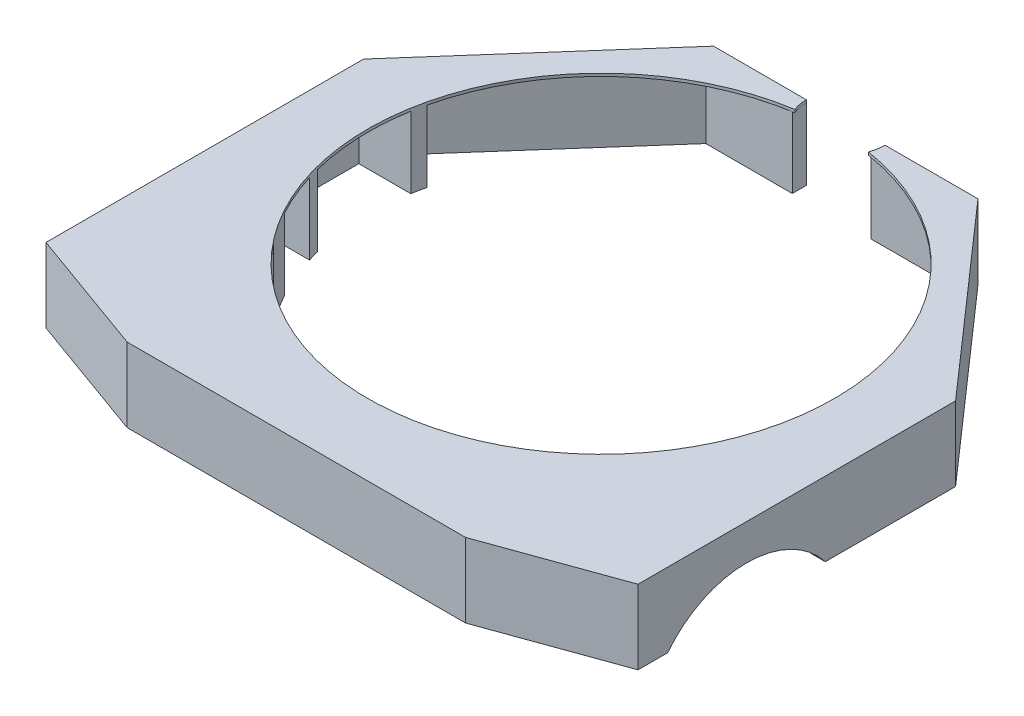
SolidWorks part; units mm, degrees
ref_plane "Front Plane" through (0, 0, 0) normal (0, 0, 1) x (1, 0, 0)
ref_plane "Top Plane" through (0, 0, 0) normal (0, 1, 0) x (1, 0, 0)
ref_plane "Right Plane" through (0, 0, 0) normal (1, 0, 0) x (0, 0, -1)
sketch "Sketch1" plane through (0, 0, 0) normal (0, 1, 0) x (1, 0, 0)
  line L0 (-304.5074, 63.6631) -> (-304.5074, -102.7433)
  line L1 (-304.5074, -102.7433) -> (-191.8567, -143.3381)
  line L2 (-191.8567, -143.3381) -> (108.842, -143.3381)
  line L3 (108.842, -143.3381) -> (221.4926, -102.7433)
  line L4 (221.4926, -102.7433) -> (221.4926, 63.6631)
  line L5 (-304.5074, 63.6631) -> (-302.0074, 63.6631)
  line L6 (-302.0074, -100.9868) -> (-191.42, -140.8381)
  line L7 (-191.42, -140.8381) -> (108.4053, -140.8381)
  line L8 (108.4053, -140.8381) -> (218.9926, -100.9868)
  line L9 (218.9926, -100.9868) -> (218.9926, 63.6631)
  line L10 (221.4926, 63.6631) -> (218.9926, 63.6631)
  line L11 (-302.0074, -100.9868) -> (-302.0074, 63.6631)
  dimension "D1" = 2.5
  dimension "D2" = 2.5
  dimension "D3" = 166.4064
  dimension "D4" = 2.5
  dimension "D5" = 2.5
  dimension "D6" = 2.5
  dimension "D7" = 119.7418
  dimension "D8" = 119.7418
  dimension "D9" = 300.6987
  dimension "D10" = 160.183
extrude "Boss-Extrude1" add sketch "Sketch1" along normal blind 63.4
sketch "Sketch2" plane through (-304.5074, 0, 0) normal (-1, 0, 0) x (0, 0, 1)
  line L2 (-63.6631, 0) -> (102.7433, 0) construction
  line L4 (102.7433, 0) -> (76.3394, 0)
  circle A1 centre (6.3381, -54.8) radius 88.9
  line M1 (-63.6631, 0) -> (102.7433, 0)
  dimension "D1" = 177.8
  dimension "D3" = 26.404
sketch "Sketch3" plane through (0, 0, 0) normal (0, 1, 0) x (1, 0, 0)
  line L1 (-304.5074, 179.4163) -> (-159.0118, 344.8175)
  line L2 (221.4926, 179.4163) -> (75.9971, 344.8175)
  line L16 (-304.5074, 63.6631) -> (-304.5074, 179.4163)
  line L17 (221.4926, 63.6631) -> (221.4926, 179.4163)
  line L19 (-159.0118, 344.8175) -> (75.9971, 344.8175)
  line L20 (-302.0074, 63.6631) -> (-302.0074, 178.4732)
  line L21 (-302.0074, 178.4732) -> (-157.8814, 342.3175)
  line L22 (-157.8814, 342.3175) -> (74.8666, 342.3175)
  line L23 (218.9926, 178.4732) -> (74.8666, 342.3175)
  line L24 (218.9926, 63.6631) -> (218.9926, 178.4732)
  line L25 (-304.5074, 63.6631) -> (-302.0074, 63.6631)
  line L26 (218.9926, 63.6631) -> (221.4926, 63.6631)
  dimension "D1" = 115.7533
  dimension "D2" = 220.2873
  dimension "D3" = 221.337
  dimension "D4" = 221.337
  dimension "D5" = 2.5
extrude "Boss-Extrude2" add sketch "Sketch3" along normal up to surface (63.4 mm away) separate body contours L17 L2 L19 L1 L16 L25 L20 L21 L22 L23 L24 L26 up to face at (-41.5074, 63.4, 60.0967)
sketch "Sketch5" plane through (0, 0, 0) normal (0, 1, 0) x (1, 0, 0)
  line L25 (208.9926, 174.7009) -> (208.9926, 63.6631)
  line L26 (70.3448, 332.3175) -> (208.9926, 174.7009)
  line L27 (-153.3595, 332.3175) -> (70.3448, 332.3175)
  line L28 (-292.0074, 174.7009) -> (-153.3595, 332.3175)
  line L29 (-292.0074, 63.6631) -> (-292.0074, 174.7009)
  line L30 (208.9926, 174.7009) -> (208.9926, 63.6631)
  line L31 (70.3448, 332.3175) -> (208.9926, 174.7009)
  line L32 (-153.3595, 332.3175) -> (70.3448, 332.3175)
  line L33 (-292.0074, 174.7009) -> (-153.3595, 332.3175)
  line L34 (-292.0074, 63.6631) -> (-292.0074, 174.7009)
  line L45 (-302.0074, 63.6631) -> (-292.0074, 63.6631)
  line L46 (208.9926, 63.6631) -> (218.9926, 63.6631)
  line L50 (218.9926, 178.4732) -> (218.9926, 63.6631)
  line L51 (74.8666, 342.3175) -> (218.9926, 178.4732)
  line L52 (-157.8814, 342.3175) -> (74.8666, 342.3175)
  line L53 (-302.0074, 178.4732) -> (-157.8814, 342.3175)
  line L54 (-302.0074, 63.6631) -> (-302.0074, 178.4732)
  line L55 (218.9926, 178.4732) -> (218.9926, 63.6631)
  line L56 (74.8666, 342.3175) -> (218.9926, 178.4732)
  line L57 (-157.8814, 342.3175) -> (74.8666, 342.3175)
  line L58 (-302.0074, 178.4732) -> (-157.8814, 342.3175)
  line L59 (-302.0074, 63.6631) -> (-302.0074, 178.4732)
  line L63 (215.6024, -91.5791) -> (106.6585, -130.8381)
  line L64 (106.6585, -130.8381) -> (-189.6732, -130.8381)
  line L65 (-189.6732, -130.8381) -> (-298.6172, -91.5791)
  line L66 (218.9926, -100.9868) -> (108.4053, -140.8381)
  line L67 (108.4053, -140.8381) -> (-191.42, -140.8381)
  line L68 (-191.42, -140.8381) -> (-302.0074, -100.9868)
  line L69 (218.9926, -100.9868) -> (108.4053, -140.8381)
  line L70 (108.4053, -140.8381) -> (-191.42, -140.8381)
  line L71 (-191.42, -140.8381) -> (-302.0074, -100.9868)
  line L72 (-298.6172, -91.5791) -> (-302.0074, -100.9868)
  line L73 (215.6024, -91.5791) -> (218.9926, -100.9868)
  dimension "D1" = 10
  dimension "D2" = 0
  dimension "D3" = 0
  dimension "D4" = 10
extrude "Boss-Extrude3" add sketch "Sketch5" along normal blind 5
sketch "Sketch6" plane through (0, 63.4, 0) normal (0, 1, 0) x (1, 0, 0)
  line L16 (-159.0118, 344.8175) -> (-304.5074, 179.4163)
  line L17 (-304.5074, 179.4163) -> (-304.5074, -102.7433)
  line L18 (-304.5074, -102.7433) -> (-191.8567, -143.3381)
  line L19 (-191.8567, -143.3381) -> (108.842, -143.3381)
  line L20 (108.842, -143.3381) -> (221.4926, -102.7433)
  line L21 (221.4926, -102.7433) -> (221.4926, 179.4163)
  line L22 (221.4926, 179.4163) -> (75.9971, 344.8175)
  line L23 (75.9971, 344.8175) -> (-159.0118, 344.8175)
  line L24 (-159.0118, 344.8175) -> (-304.5074, 179.4163)
  line L25 (-304.5074, 179.4163) -> (-304.5074, -102.7433)
  line L26 (-304.5074, -102.7433) -> (-191.8567, -143.3381)
  line L27 (-191.8567, -143.3381) -> (108.842, -143.3381)
  line L28 (108.842, -143.3381) -> (221.4926, -102.7433)
  line L29 (221.4926, -102.7433) -> (221.4926, 179.4163)
  line L30 (221.4926, 179.4163) -> (75.9971, 344.8175)
  line L31 (75.9971, 344.8175) -> (-159.0118, 344.8175)
  dimension "D1" = 0
extrude "Boss-Extrude4" add sketch "Sketch6" along normal blind 2.5
sketch "Sketch7" plane through (0, 5, 0) normal (0, 1, 0) x (1, 0, 0)
  line L0 (106.6585, -130.8381) -> (-189.6732, -130.8381) construction
  line L1 (-52.15, -130.8381) -> (-42.15, -130.8381)
  line L2 (-52.15, -130.8381) -> (-52.15, -140.8381)
  line L3 (-52.15, -140.8381) -> (-42.15, -140.8381)
  line L4 (-42.15, -130.8381) -> (-42.15, -140.8381)
  line L5 (-191.42, -140.8381) -> (108.4053, -140.8381) construction
  line L7 (76.7898, -130.8381) -> (86.7898, -130.8381)
  line L8 (76.7898, -130.8381) -> (76.7898, -140.8381)
  line L9 (76.7898, -140.8381) -> (86.7898, -140.8381)
  line L10 (86.7898, -130.8381) -> (86.7898, -140.8381)
  line L11 (-257.8308, -106.2769) -> (-261.221, -115.6847)
  line L12 (-178.361, -130.8381) -> (-168.361, -130.8381)
  line L13 (-178.361, -130.8381) -> (-178.361, -140.8381)
  line L14 (-178.361, -140.8381) -> (-168.361, -140.8381)
  line L15 (-168.361, -130.8381) -> (-168.361, -140.8381)
  line L16 (-189.6732, -130.8381) -> (-298.6172, -91.5791) construction
  line L17 (-302.0074, -100.9868) -> (-191.42, -140.8381) construction
  line L18 (-248.423, -109.6671) -> (-251.8132, -119.0748)
  line L19 (-251.8132, -119.0748) -> (-261.221, -115.6847)
  line L20 (-257.8308, -106.2769) -> (-248.423, -109.6671)
  line L21 (155.7814, -113.1362) -> (159.1716, -122.544)
  line L22 (215.6024, -91.5791) -> (106.6585, -130.8381) construction
  line L24 (159.1716, -122.544) -> (168.5794, -119.1538)
  line L25 (108.4053, -140.8381) -> (218.9926, -100.9868) construction
  line L26 (168.5794, -119.1538) -> (165.1892, -109.746)
  line L27 (165.1892, -109.746) -> (155.7814, -113.1362)
  line L28 (-302.0074, 178.4732) -> (-302.0074, 63.6631) construction
  line L34 (74.8666, 342.3175) -> (-157.8814, 342.3175) construction
  line L35 (-127.9155, 342.3175) -> (-117.9155, 342.3175)
  line L36 (-127.9155, 342.3175) -> (-127.9155, 332.3175)
  line L37 (-127.9155, 332.3175) -> (-117.9155, 332.3175)
  line L38 (-117.9155, 342.3175) -> (-117.9155, 332.3175)
  line L39 (-153.3595, 332.3175) -> (70.3448, 332.3175) construction
  line L41 (18.9775, 342.3175) -> (28.9775, 342.3175)
  line L42 (18.9775, 342.3175) -> (18.9775, 332.3175)
  line L43 (18.9775, 332.3175) -> (28.9775, 332.3175)
  line L44 (28.9775, 342.3175) -> (28.9775, 332.3175)
  line L45 (208.9926, 174.7009) -> (208.9926, 63.6631) construction
  line L46 (208.9926, 174.7009) -> (218.9926, 174.7009)
  line L47 (208.9926, 174.7009) -> (208.9926, 164.7009)
  line L48 (208.9926, 164.7009) -> (218.9926, 164.7009)
  line L49 (218.9926, 174.7009) -> (218.9926, 164.7009)
  line L50 (218.9926, 63.6631) -> (218.9926, 178.4732) construction
  line L51 (-263.7563, 221.9576) -> (-256.2478, 215.3528)
  line L52 (208.9926, 63.6631) -> (218.9926, 63.6631)
  line L53 (208.9926, 63.6631) -> (208.9926, 73.6631)
  line L54 (208.9926, 73.6631) -> (218.9926, 73.6631)
  line L55 (218.9926, 63.6631) -> (218.9926, 73.6631)
  line L56 (-292.0074, 63.6631) -> (-302.0074, 63.6631)
  line L57 (-292.0074, 63.6631) -> (-292.0074, 73.6631)
  line L58 (-292.0074, 73.6631) -> (-302.0074, 73.6631)
  line L59 (-302.0074, 63.6631) -> (-302.0074, 73.6631)
  line L60 (-292.0074, 174.7009) -> (-302.0074, 174.7009)
  line L61 (-292.0074, 174.7009) -> (-292.0074, 164.7009)
  line L62 (-292.0074, 164.7009) -> (-302.0074, 164.7009)
  line L63 (-302.0074, 174.7009) -> (-302.0074, 164.7009)
  line L64 (-157.8814, 342.3175) -> (-302.0074, 178.4732) construction
  line L65 (-292.0074, 174.7009) -> (-153.3595, 332.3175) construction
  line L66 (-256.2478, 215.3528) -> (-249.643, 222.8612)
  line L67 (-249.643, 222.8612) -> (-257.1515, 229.466)
  line L68 (-257.1515, 229.466) -> (-263.7563, 221.9576)
  line L69 (-209.6632, 283.4513) -> (-202.1548, 276.8465)
  line L71 (-202.1548, 276.8465) -> (-195.55, 284.3549)
  line L72 (-195.55, 284.3549) -> (-203.0584, 290.9597)
  line L73 (-203.0584, 290.9597) -> (-209.6632, 283.4513)
  line L74 (116.6943, 294.7673) -> (109.1858, 288.1625)
  line L76 (70.3448, 332.3175) -> (208.9926, 174.7009) construction
  line L77 (109.1858, 288.1625) -> (115.7906, 280.6541)
  line L78 (115.7906, 280.6541) -> (123.2991, 287.2589)
  line L79 (218.9926, 178.4732) -> (74.8666, 342.3175) construction
  line L80 (123.2991, 287.2589) -> (116.6943, 294.7673)
  line L81 (174.6268, 228.9089) -> (167.1183, 222.3041)
  line L82 (167.1183, 222.3041) -> (173.7231, 214.7957)
  line L83 (173.7231, 214.7957) -> (181.2316, 221.4005)
  line L84 (181.2316, 221.4005) -> (174.6268, 228.9089)
  dimension "D1" = 10
  dimension "D2" = 10
  dimension "D3" = 10
  dimension "D4" = 10
  dimension "D5" = 10
  dimension "D6" = 10
  dimension "D7" = 10
  dimension "D8" = 10
  dimension "D9" = 10
  dimension "D10" = 10
  dimension "D11" = 10
  dimension "D12" = 10
  dimension "D13" = 10
  dimension "D14" = 10
  dimension "D15" = 10
extrude "Boss-Extrude5" [suppressed] add sketch "Sketch7" along normal up to surface (58.4 mm away)
sketch "Sketch8" plane through (0, 0, -344.8175) normal (0, 0, -1) x (-1, 0, 0)
  line L0 (268.4856, 0) -> (-268.4856, 0) construction
  line L1 (6.5074, 0) -> (76.5074, 0)
  line L2 (6.5074, 0) -> (6.5074, 28.4)
  line L3 (6.5074, 28.4) -> (76.5074, 28.4)
  line L4 (76.5074, 0) -> (76.5074, 28.4)
  line L5 (-75.9971, 0) -> (6.5074, 0) construction
  line L6 (16.5074, 28.4) -> (66.5074, 28.4)
  line L7 (16.5074, 28.4) -> (16.5074, 63.4)
  line L8 (16.5074, 63.4) -> (66.5074, 63.4)
  line L9 (66.5074, 28.4) -> (66.5074, 63.4)
  line L10 (76.5074, 0) -> (159.0118, 0) construction
  line L12 (6.5074, 28.4) -> (16.5074, 28.4) construction
  line L13 (6.5074, 28.4) -> (6.5074, 37.3454) construction
  line L14 (6.5074, 37.3454) -> (16.5074, 37.3454) construction
  line L15 (16.5074, 28.4) -> (16.5074, 37.3454) construction
  line L16 (66.5074, 28.4) -> (76.5074, 28.4) construction
  line L17 (66.5074, 28.4) -> (66.5074, 37.3454) construction
  line L18 (66.5074, 37.3454) -> (76.5074, 37.3454) construction
  line L19 (76.5074, 28.4) -> (76.5074, 37.3454) construction
  line M4 (-75.9971, 0) -> (159.0118, 0)
  dimension "D1" = 70
  dimension "D2" = 50
  dimension "D3" = 63.4
  dimension "D4" = 28.4
extrude "Cut-Extrude2" cut sketch "Sketch8" along direction (0, 0, -1) on the side against the normal up to next (12.5 mm away) contours L4 L3 L2 M4 | L3 L9 L8 L7
sketch "Sketch9" plane through (0, 65.9, 0) normal (0, 1, 0) x (1, 0, 0)
  line L16 (75.9971, 344.8175) -> (-159.0118, 344.8175)
  line L17 (-159.0118, 344.8175) -> (-304.5074, 179.4163)
  line L18 (-304.5074, 179.4163) -> (-304.5074, -102.7433)
  line L19 (-304.5074, -102.7433) -> (-191.8567, -143.3381)
  line L20 (-191.8567, -143.3381) -> (108.842, -143.3381)
  line L21 (108.842, -143.3381) -> (221.4926, -102.7433)
  line L22 (221.4926, -102.7433) -> (221.4926, 179.4163)
  line L23 (221.4926, 179.4163) -> (75.9971, 344.8175)
  line L24 (75.9971, 344.8175) -> (-159.0118, 344.8175) construction
  line L25 (-159.0118, 344.8175) -> (-304.5074, 179.4163)
  line L26 (-304.5074, 179.4163) -> (-304.5074, -102.7433)
  line L27 (-304.5074, -102.7433) -> (-191.8567, -143.3381)
  line L28 (-191.8567, -143.3381) -> (108.842, -143.3381)
  line L29 (108.842, -143.3381) -> (221.4926, -102.7433)
  line L30 (221.4926, -102.7433) -> (221.4926, 179.4163)
  line L31 (221.4926, 179.4163) -> (75.9971, 344.8175)
  line L33 (-6.5074, 344.8175) -> (-16.5074, 344.8175)
  line L34 (-16.5074, 344.8175) -> (-66.5074, 344.8175)
  line L35 (-66.5074, 344.8175) -> (-76.5074, 344.8175)
  line L36 (-6.5074, 344.8175) -> (-16.5074, 344.8175) construction
  line L37 (-16.5074, 344.8175) -> (-66.5074, 344.8175) construction
  line L38 (-66.5074, 344.8175) -> (-76.5074, 344.8175) construction
  circle A0 centre (-41.5074, 344.8175) radius 35
  line M13 (75.9971, 344.8175) -> (-159.0118, 344.8175)
  dimension "D1" = 0
  dimension "D2" = 0
extrude "Cut-Extrude4" cut sketch "Sketch9" against normal up to surface (2.5 mm away) contours A0 M13
sketch "Sketch10" plane through (0, 0, -344.8175) normal (0, 0, -1) x (-1, 0, 0)
  line L1 (6.5074, 63.4) -> (16.5074, 63.4)
  line L2 (6.5074, 63.4) -> (6.5074, 28.4)
  line L3 (6.5074, 28.4) -> (16.5074, 28.4)
  line L4 (16.5074, 63.4) -> (16.5074, 28.4)
  line L5 (66.5074, 63.4) -> (76.5074, 63.4)
  line L6 (66.5074, 63.4) -> (66.5074, 28.4)
  line L7 (66.5074, 28.4) -> (76.5074, 28.4)
  line L8 (76.5074, 63.4) -> (76.5074, 28.4)
extrude "Cut-Extrude5" cut sketch "Sketch10" against normal up to surface (2.5 mm away) up to face at (13.8724, 36.7143, -342.3175)
sketch "Sketch11" plane through (0, 5, 0) normal (0, 1, 0) x (1, 0, 0)
  line L526 (-76.5074, 332.3175) -> (-76.5074, 342.3175)
  line L527 (-76.5074, 342.3175) -> (-157.8814, 342.3175)
  line L528 (-153.3595, 332.3175) -> (-76.5074, 332.3175)
  line L529 (-292.0074, 174.7009) -> (-153.3595, 332.3175)
  line L530 (-157.8814, 342.3175) -> (-302.0074, 178.4732)
  line L531 (-302.0074, 178.4732) -> (-302.0074, 63.6631)
  line L532 (-292.0074, 63.6631) -> (-292.0074, 174.7009)
  line L533 (-302.0074, 63.6631) -> (-292.0074, 63.6631)
  line L534 (-76.5074, 332.3175) -> (-76.5074, 342.3175)
  line L535 (-76.5074, 342.3175) -> (-157.8814, 342.3175)
  line L536 (-153.3595, 332.3175) -> (-76.5074, 332.3175)
  line L537 (-292.0074, 174.7009) -> (-153.3595, 332.3175)
  line L538 (-157.8814, 342.3175) -> (-302.0074, 178.4732)
  line L539 (-302.0074, 178.4732) -> (-302.0074, 63.6631)
  line L540 (-292.0074, 63.6631) -> (-292.0074, 174.7009)
  line L541 (-302.0074, 63.6631) -> (-292.0074, 63.6631)
  line L578 (208.9926, 63.6631) -> (218.9926, 63.6631)
  line L579 (218.9926, 63.6631) -> (218.9926, 178.4732)
  line L580 (208.9926, 174.7009) -> (208.9926, 63.6631)
  line L581 (218.9926, 178.4732) -> (74.8666, 342.3175)
  line L582 (70.3448, 332.3175) -> (208.9926, 174.7009)
  line L583 (74.8666, 342.3175) -> (-6.5074, 342.3175)
  line L584 (-6.5074, 332.3175) -> (70.3448, 332.3175)
  line L585 (-6.5074, 342.3175) -> (-6.5074, 332.3175)
  line L586 (208.9926, 63.6631) -> (218.9926, 63.6631)
  line L587 (218.9926, 63.6631) -> (218.9926, 178.4732)
  line L588 (208.9926, 174.7009) -> (208.9926, 63.6631)
  line L589 (218.9926, 178.4732) -> (74.8666, 342.3175)
  line L590 (70.3448, 332.3175) -> (208.9926, 174.7009)
  line L591 (74.8666, 342.3175) -> (-6.5074, 342.3175)
  line L592 (-6.5074, 332.3175) -> (70.3448, 332.3175)
  line L593 (-6.5074, 342.3175) -> (-6.5074, 332.3175)
  line L595 (108.4053, -140.8381) -> (218.9926, -100.9868)
  line L596 (218.9926, -100.9868) -> (215.6024, -91.5791)
  line L597 (215.6024, -91.5791) -> (106.6585, -130.8381)
  line L598 (108.4053, -140.8381) -> (218.9926, -100.9868)
  line L599 (218.9926, -100.9868) -> (215.6024, -91.5791)
  line L600 (215.6024, -91.5791) -> (106.6585, -130.8381)
  line L621 (-302.0074, -100.9868) -> (-191.42, -140.8381)
  line L622 (-189.6732, -130.8381) -> (-298.6172, -91.5791)
  line L623 (-298.6172, -91.5791) -> (-302.0074, -100.9868)
  line L624 (-191.42, -140.8381) -> (108.4053, -140.8381)
  line L625 (106.6585, -130.8381) -> (-189.6732, -130.8381)
  line L626 (-302.0074, -100.9868) -> (-191.42, -140.8381)
  line L627 (-189.6732, -130.8381) -> (-298.6172, -91.5791)
  line L628 (-298.6172, -91.5791) -> (-302.0074, -100.9868)
  line L629 (-191.42, -140.8381) -> (108.4053, -140.8381)
  line L630 (106.6585, -130.8381) -> (-189.6732, -130.8381)
  dimension "D1" = 0
  dimension "D2" = 0
  dimension "D3" = 0
  dimension "D4" = 0
extrude "Boss-Extrude6" add sketch "Sketch11" along normal up to surface (58.4 mm away) up to face at (-41.5074, 63.4, -158.1001)
sketch "Sketch12" plane through (0, 0, 0) normal (0, -1, 0) x (1, 0, 0)
  line L0 (-302.0074, 100.9868) -> (-302.0074, -63.6631)
  line L1 (-302.0074, -63.6631) -> (-292.0074, -63.6631)
  line L2 (-292.0074, -63.6631) -> (-292.0074, 93.961)
  line L3 (-189.6732, 130.8381) -> (-298.6172, 91.5791) construction
  line L4 (-292.0074, 93.961) -> (-298.6172, 91.5791)
  line L5 (-298.6172, 91.5791) -> (-302.0074, 100.9868)
  line L6 (218.9926, 100.9868) -> (218.9926, -63.6631)
  line L7 (218.9926, -63.6631) -> (208.9926, -63.6631)
  line L8 (208.9926, -63.6631) -> (208.9926, 93.961)
  line L9 (215.6024, 91.5791) -> (106.6585, 130.8381) construction
  line L10 (208.9926, 93.961) -> (215.6024, 91.5791)
  line L11 (215.6024, 91.5791) -> (218.9926, 100.9868)
extrude "Boss-Extrude7" add sketch "Sketch12" against normal up to surface (63.4 mm away) up to face at (-41.5074, 63.4, -107.8417)
extrude "Cut-Extrude8" cut sketch "Sketch2" against normal through all both and the other way through all contours A1 M1 | A1 M1
sketch "Sketch13" plane through (0, 65.9, 0) normal (0, 1, 0) x (1, 0, 0)
  line L0 (-76.5074, 344.8175) -> (-6.5074, 344.8175) construction
  circle A0 centre (-41.5074, 127.4496) radius 217.3679 construction
  circle A1 centre (-41.5074, 127.4496) radius 207.3679
  point P6 (-41.5074, 344.8175)
  dimension "D1" = 10
extrude "Cut-Extrude9" cut sketch "Sketch13" against normal through all
sketch "Sketch16" plane through (0, 63.4, 0) normal (0, -1, 0) x (1, 0, 0)
  line L0 (-292.0074, -174.7009) -> (-243.4202, -174.7009)
  line L1 (-292.0074, -174.7009) -> (-292.0074, -162.7009)
  line L2 (-292.0074, 93.961) -> (-292.0074, -174.7009) construction
  line L3 (-292.0074, -162.7009) -> (-245.8571, -162.7009)
  line L4 (-292.0074, -66.6564) -> (-239.7639, -66.6564)
  line L5 (-292.0074, -66.6564) -> (-292.0074, -76.6564)
  line L6 (-292.0074, -76.6564) -> (-242.5584, -76.6564)
  line L7 (-223.5136, 118.6434) -> (-223.5136, -28.0755)
  line L8 (-189.6732, 130.8381) -> (-292.0074, 93.961) construction
  line L9 (-223.5136, 118.6434) -> (-204.698, 125.4238)
  line L10 (-189.6732, 130.8381) -> (-292.0074, 93.961) construction
  line L11 (-204.698, 125.4238) -> (-204.698, 0.4969)
  line L12 (-189.6732, 130.8381) -> (-189.6732, 17.6309)
  line L13 (-189.6732, 130.8381) -> (106.6585, 130.8381)
  line L14 (106.6585, 130.8381) -> (106.6585, 17.6309)
  line L15 (91.6585, 115.8381) -> (91.6585, 31.5106)
  line L16 (-174.6732, 115.8381) -> (-174.6732, 31.5106)
  line L17 (-174.6732, 115.8381) -> (91.6585, 115.8381)
  line L18 (121.6832, 125.4238) -> (121.6832, 0.4969)
  line L19 (208.9926, 93.961) -> (106.6585, 130.8381) construction
  line L20 (121.6832, 125.4238) -> (140.4988, 118.6434)
  line L21 (208.9926, 93.961) -> (106.6585, 130.8381) construction
  line L22 (140.4988, 118.6434) -> (140.4988, -28.0755)
  line L23 (208.9926, -66.6564) -> (156.7492, -66.6564)
  line L24 (208.9926, -174.7009) -> (208.9926, 93.961) construction
  line L25 (208.9926, -66.6564) -> (208.9926, -75.9843)
  line L26 (208.9926, -174.7009) -> (208.9926, -63.6631) construction
  line L27 (208.9926, -75.9843) -> (159.3727, -75.9843)
  line L28 (208.9926, -174.7009) -> (160.4054, -174.7009)
  line L29 (208.9926, -174.7009) -> (208.9926, -162.7009)
  line L30 (208.9926, -162.7009) -> (162.8423, -162.7009)
  arc A0 (-8.8493, -332.2297) -> (-74.1654, -332.2297) centre (-41.5074, -127.4496) ccw construction
  arc A1 (-243.4202, -174.7009) -> (-245.8571, -162.7009) centre (-41.5074, -127.4496) cw
  arc A2 (-242.5584, -76.6564) -> (-239.7639, -66.6564) centre (-41.5074, -127.4496) cw
  arc A3 (-223.5136, -28.0755) -> (-204.698, 0.4969) centre (-41.5074, -127.4496) cw
  arc A4 (-189.6732, 17.6309) -> (-174.6732, 31.5106) centre (-41.5074, -127.4496) cw
  arc A5 (91.6585, 31.5106) -> (106.6585, 17.6309) centre (-41.5074, -127.4496) cw
  arc A6 (121.6832, 0.4969) -> (140.4988, -28.0755) centre (-41.5074, -127.4496) cw
  arc A7 (156.7492, -66.6564) -> (159.3727, -75.9843) centre (-41.5074, -127.4496) cw
  arc A8 (162.8423, -162.7009) -> (160.4054, -174.7009) centre (-41.5074, -127.4496) cw
  dimension "D1" = 12
  dimension "D2" = 10
  dimension "D3" = 20
  dimension "D4" = 15
  dimension "D5" = 15
  dimension "D6" = 15
extrude "Boss-Extrude15" add sketch "Sketch16" along normal through all
